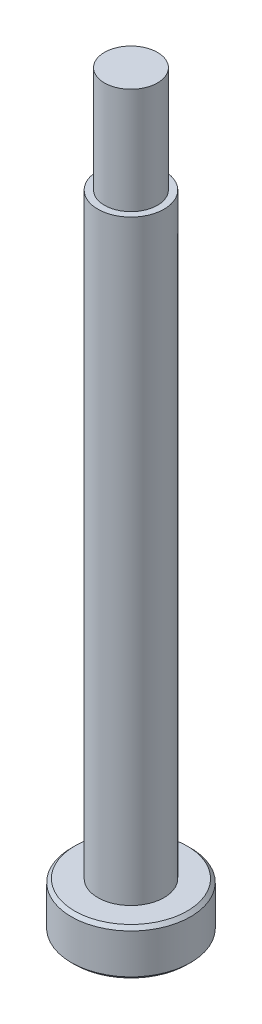
SolidWorks part; units mm, degrees
material "AISI 304"
ref_plane "前视基准面" through (0, 0, 0) normal (0, 0, 1) x (1, 0, 0)
ref_plane "上视基准面" through (0, 0, 0) normal (0, 1, 0) x (1, 0, 0)
ref_plane "右视基准面" through (0, 0, 0) normal (1, 0, 0) x (0, 0, -1)
other "Configuration Table"
sketch "草图1" plane through (0, 0, 0) normal (0, 1, 0) x (1, 0, 0)
  circle A0 centre (0, 0) radius 4.5
  dimension "D1" = 9
extrude "凸台-拉伸1" add sketch "草图1" against normal blind 3.5
sketch "草图2" plane through (0, 0, 0) normal (0, 1, 0) x (1, 0, 0)
  circle A0 centre (0, 0) radius 2.5
  dimension "D1" = 5
extrude "凸台-拉伸2" add sketch "草图2" along normal blind 45
sketch "草图3" plane through (0, 45, 0) normal (0, 1, 0) x (1, 0, 0)
  circle A0 centre (0, 0) radius 2
  dimension "D1" = 4
extrude "凸台-拉伸3" add sketch "草图3" along normal blind 8
sketch "草图4" plane through (0, -3.5, 0) normal (0, -1, 0) x (1, 0, 0)
  line L1 (1.5, -0.866) -> (1.5, 0.866)
  line L2 (1.5, 0.866) -> (0, 1.7321)
  line L3 (0, 1.7321) -> (-1.5, 0.866)
  line L4 (-1.5, 0.866) -> (-1.5, -0.866)
  line L5 (-1.5, -0.866) -> (0, -1.7321)
  line L6 (0, -1.7321) -> (1.5, -0.866)
  circle A0 centre (0, 0) radius 1.5 construction
  dimension "D1" = 3
extrude "切除-拉伸1" cut sketch "草图4" against normal blind 2.5
chamfer "倒角1" distance 0.25 angle 45 2 edges at (0, -3.5, 4.5) (0, 0, 4.5)
